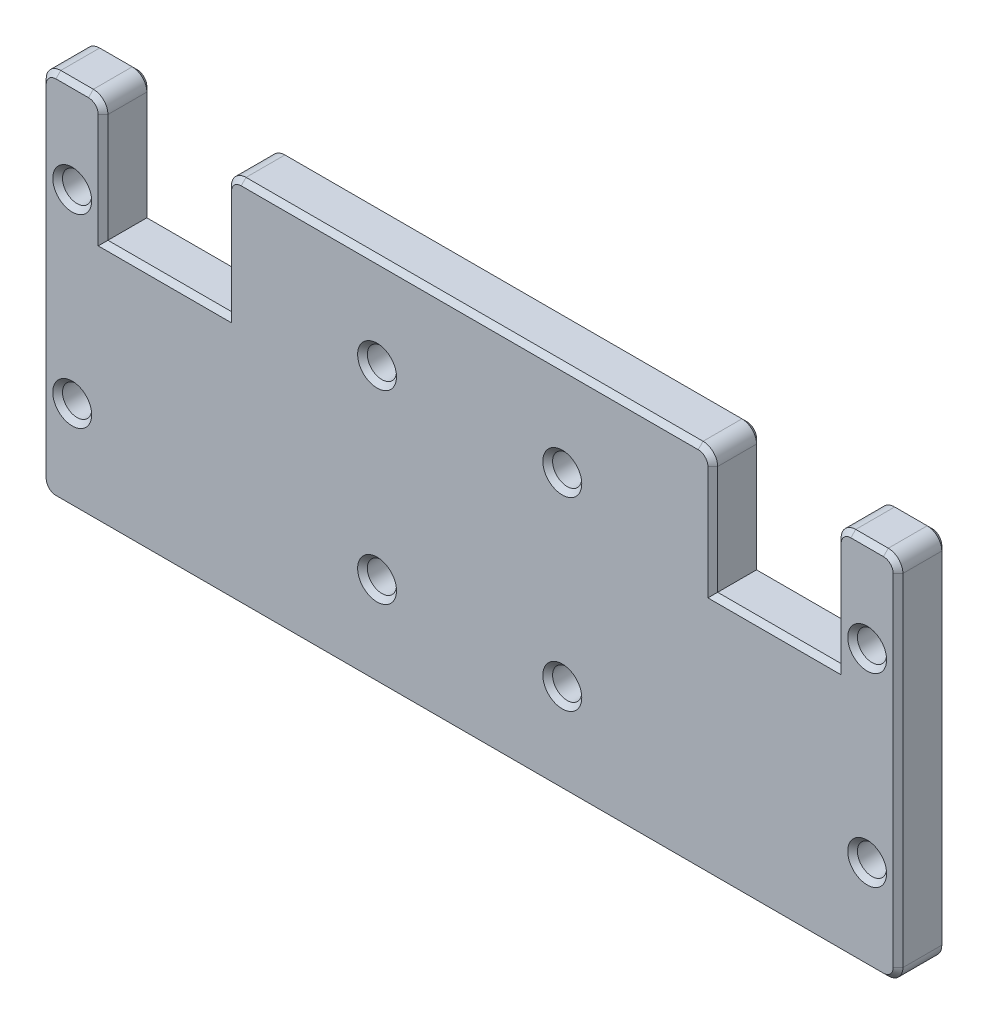
SolidWorks part; units mm, degrees
ref_plane "Front Plane" through (0, 0, 0) normal (0, 0, 1) x (1, 0, 0)
ref_plane "Top Plane" through (0, 0, 0) normal (0, 1, 0) x (1, 0, 0)
ref_plane "Right Plane" through (0, 0, 0) normal (1, 0, 0) x (0, 0, -1)
sketch "Sketch1" plane through (0, 0, 0) normal (0, 0, 1) x (1, 0, 0)
  line L0 (75.4, 25.4) -> (50, 25.4)
  line L6 (-50, 47.8) -> (-50, 25.4)
  line L7 (-50, 25.4) -> (-75.4, 25.4)
  line L8 (-75.4, 47.8) -> (-75.4, 25.4)
  line L9 (-50, 50.8) -> (-75.4, 25.4) construction
  line L10 (-50, 25.4) -> (-75.4, 50.8) construction
  line L11 (50, 47.8) -> (50, 25.4)
  line L13 (75.4, 47.8) -> (75.4, 25.4)
  line L14 (75.4, 50.8) -> (50, 25.4) construction
  line L15 (75.4, 25.4) -> (50, 50.8) construction
  line L16 (-78.4, 50.8) -> (-85.1, 50.8)
  line L17 (-88.1, 47.8) -> (-88.1, -22.4)
  line L18 (78.4, 50.8) -> (85.1, 50.8)
  line L19 (88.1, 47.8) -> (88.1, -22.4)
  line L20 (85.1, -25.4) -> (-85.1, -25.4)
  line L21 (-47, 50.8) -> (47, 50.8)
  arc A0 (-88.1, -22.4) -> (-85.1, -25.4) centre (-85.1, -22.4) ccw
  arc A1 (85.1, -25.4) -> (88.1, -22.4) centre (85.1, -22.4) ccw
  arc A2 (88.1, 47.8) -> (85.1, 50.8) centre (85.1, 47.8) ccw
  arc A3 (75.4, 47.8) -> (78.4, 50.8) centre (78.4, 47.8) cw
  arc A4 (50, 47.8) -> (47, 50.8) centre (47, 47.8) ccw
  arc A5 (-47, 50.8) -> (-50, 47.8) centre (-47, 47.8) ccw
  arc A6 (-75.4, 47.8) -> (-78.4, 50.8) centre (-78.4, 47.8) ccw
  arc A7 (-85.1, 50.8) -> (-88.1, 47.8) centre (-85.1, 47.8) ccw
  circle A8 centre (-19.05, 31.75) radius 3
  circle A9 centre (19.05, 31.75) radius 3
  circle A10 centre (19.05, -6.35) radius 3
  circle A11 centre (-19.05, -6.35) radius 3
  circle A15 centre (-81.75, 31.75) radius 3
  circle A16 centre (-81.75, -6.35) radius 3
  circle A17 centre (81.75, -6.35) radius 3
  circle A18 centre (81.75, 31.75) radius 3
  point P0 (-62.7, 38.1)
  point P5 (62.7, 38.1)
  dimension "D1" = 3
  dimension "D2" = 2
  dimension "D3" = 2
extrude "Boss-Extrude1" add sketch "Sketch1" along normal blind 10
chamfer "Chamfer1" distance 1 angle 45 56 edges at (78.75, 31.75, 0) (78.75, -6.35, 0) (-78.75, -6.35, 0) (-16.05, -6.35, 0) (22.05, -6.35, 0) (22.05, 31.75, 0) (-78.75, 31.75, 0) (-16.05, 31.75, 0) (-76.2787, 49.9213, 0) (-81.75, 50.8, 0) (-87.2213, 49.9213, 0) (-88.1, 12.7, 0) (-87.2213, -24.5213, 0) (0, -25.4, 0) (87.2213, -24.5213, 0) (88.1, 12.7, 0) (87.2213, 49.9213, 0) (81.75, 50.8, 0) (76.2787, 49.9213, 0) (75.4, 36.6, 0) (62.7, 25.4, 0) (50, 36.6, 0) (49.1213, 49.9213, 0) (0, 50.8, 0) (-49.1213, 49.9213, 0) (-50, 36.6, 0) (-62.7, 25.4, 0) (-75.4, 36.6, 0) (78.75, 31.75, 10) (-78.75, -6.35, 10) (22.05, -6.35, 10) (-78.75, 31.75, 10) (-62.7, 25.4, 10) (-50, 36.6, 10) (-49.1213, 49.9213, 10) (0, 50.8, 10) (49.1213, 49.9213, 10) (50, 36.6, 10) (62.7, 25.4, 10) (75.4, 36.6, 10) (76.2787, 49.9213, 10) (81.75, 50.8, 10) (87.2213, 49.9213, 10) (88.1, 12.7, 10) (87.2213, -24.5213, 10) (0, -25.4, 10) (-87.2213, -24.5213, 10) (-88.1, 12.7, 10) (-87.2213, 49.9213, 10) (-81.75, 50.8, 10) (-76.2787, 49.9213, 10) (-75.4, 36.6, 10) (-16.05, 31.75, 10) (22.05, 31.75, 10) (-16.05, -6.35, 10) (78.75, -6.35, 10)
